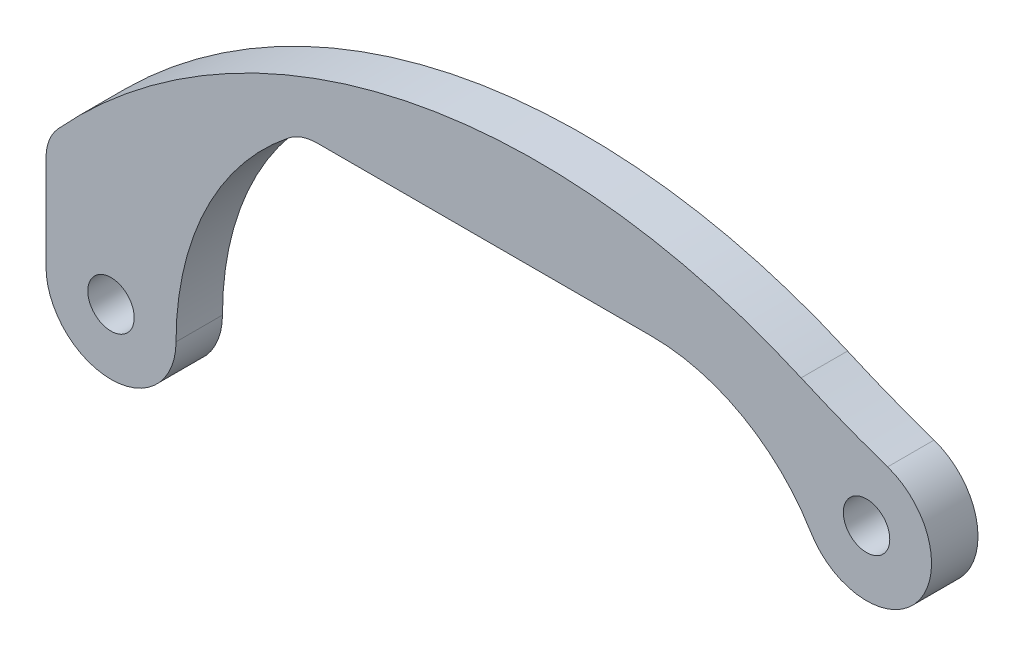
SolidWorks part; units mm, degrees
ref_plane "Front Plane" through (0, 0, 0) normal (0, 0, 1) x (1, 0, 0)
ref_plane "Top Plane" through (0, 0, 0) normal (0, 1, 0) x (1, 0, 0)
ref_plane "Right Plane" through (0, 0, 0) normal (1, 0, 0) x (0, 0, -1)
sketch "Sketch1" plane through (0, 0, 0) normal (0, 0, 1) x (1, 0, 0)
  line L0 (-30.672, -68.4445) -> (15.048, -68.4445)
  line L1 (-67.7542, -101.6368) -> (-67.7542, -88.734)
  circle A1 centre (44.45, -76.2) radius 3.175
  arc A2 (-30.672, -68.4445) -> (-34.6234, -69.8237) centre (-30.672, -74.7945) ccw
  arc A3 (35.5031, -63.1576) -> (-66.09, -84.4485) centre (-0.4888, -144.4459) ccw
  arc A4 (15.048, -68.4445) -> (36.8273, -80.7745) centre (15.048, -93.8445) cw
  arc A5 (-67.7542, -101.6368) -> (-49.9742, -101.6368) centre (-58.8642, -101.6368) ccw
  circle A6 centre (-58.8642, -101.6368) radius 3.175 construction
  circle A7 centre (-58.8642, -101.6368) radius 3.175
  circle A8 centre (-58.8642, -101.6368) radius 8.89 construction
  arc A10 (-34.6234, -69.8237) -> (-49.9742, -101.6368) centre (-9.3342, -101.6368) ccw
  circle A11 centre (44.45, -76.2) radius 8.89 construction
  arc A12 (36.8273, -80.7745) -> (47.3285, -67.7889) centre (44.45, -76.2) ccw
  arc A14 (22.4992, -66.4844) -> (-67.0334, -97.7742) centre (-0.4888, -144.4459) ccw construction
  arc A15 (35.5031, -63.1576) -> (47.3285, -67.7889) centre (94.5625, 70.229) ccw
  arc A16 (-66.09, -84.4485) -> (-67.7542, -88.734) centre (-61.4042, -88.734) ccw
  dimension "D2" = 40.64
  dimension "D3" = 88.9
  dimension "D5" = 6.35
  dimension "D1" = 6.35
  dimension "D8" = 25.4
  dimension "D10" = 45.72
  dimension "D4" = 6.35
  dimension "D6" = 12.7
extrude "Extrude1" add sketch "Sketch1" along normal mid plane 6.35
